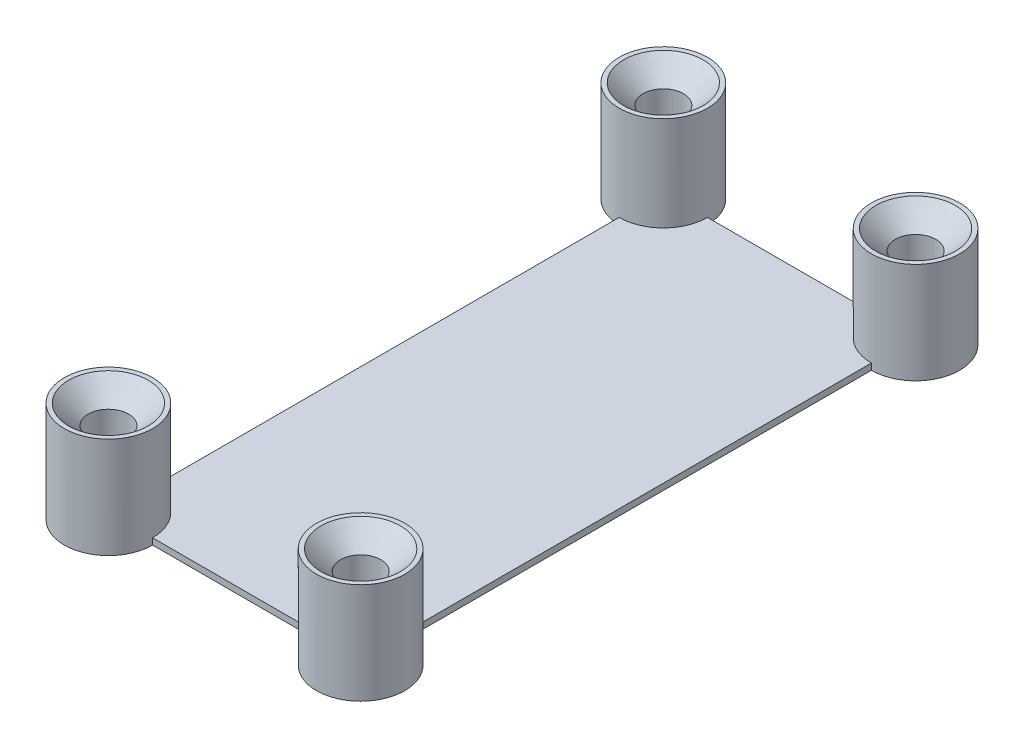
SolidWorks part; units mm, degrees
ref_plane "Front Plane" through (0, 0, 0) normal (0, 0, 1) x (1, 0, 0)
ref_plane "Top Plane" through (0, 0, 0) normal (0, 1, 0) x (1, 0, 0)
ref_plane "Right Plane" through (0, 0, 0) normal (1, 0, 0) x (0, 0, -1)
sketch "Sketch2" plane through (0, 0, 0) normal (0, 1, 0) x (1, 0, 0)
  line L0 (0, 22) -> (20, 22) construction
  line L1 (0, 0) -> (20, 0)
  line L2 (0, 0) -> (0, 44)
  line L3 (0, 44) -> (20, 44)
  line L4 (20, 0) -> (20, 44)
  line L5 (10, 44) -> (10, 0) construction
sketch "Sketch4" plane through (0, 0, 0) normal (0, 1, 0) x (1, 0, 0)
  line L0 (10, 44) -> (10, 0) construction
  line L1 (0, 22) -> (20, 22) construction
  line L2 (0, 0) -> (0, 44) construction
  circle A0 centre (20, 44) radius 3.5
  circle A1 centre (0, 44) radius 3.5
  circle A2 centre (20, 0) radius 3.5
  circle A3 centre (0, 0) radius 3.5
extrude "Boss-Extrude2" add sketch "Sketch2" along normal blind 0.5
extrude "Boss-Extrude3" add sketch "Sketch4" along normal blind 8
hole_wizard "CSK for M3 Flat Head Machine Screw1" positions "Sketch5" profile "Sketch6" countersink size "M3" standard "ANSI Metric"
sketch "Sketch5" plane through (0, 8, 0) normal (0, 1, 0) x (1, 0, 0)
  point P0 (20, 44)
  point P3 (0, 44)
  point P6 (0, 0)
  point P9 (20, 0)
sketch "Sketch6" plane through (20, 8, -44) normal (1, 0, 0) x (0, 0, 1)
  line L0 (0, 0) -> (0, 14)
  line L1 (0, 14) -> (1.6, 13.0386)
  line L2 (1.6, 13.0386) -> (1.6, 1.55)
  line L3 (1.6, 1.55) -> (3.15, 0)
  line L5 (3.15, 0) -> (0, 0)
  line L6 (-1.6, 1.55) -> (-3.15, 0) construction
  line L10 (0, 14) -> (-1.6, 13.0386) construction
  line L11 (0, -6.35) -> (0, 107.95) construction
  dimension "Hole Dia." = 3.2
  dimension "Hole Depth" = 14
  dimension "Near C'Sink Dia." = 6.3
  dimension "Near C'Sink Angle" = 90
  dimension "Drill Angle" = 118
